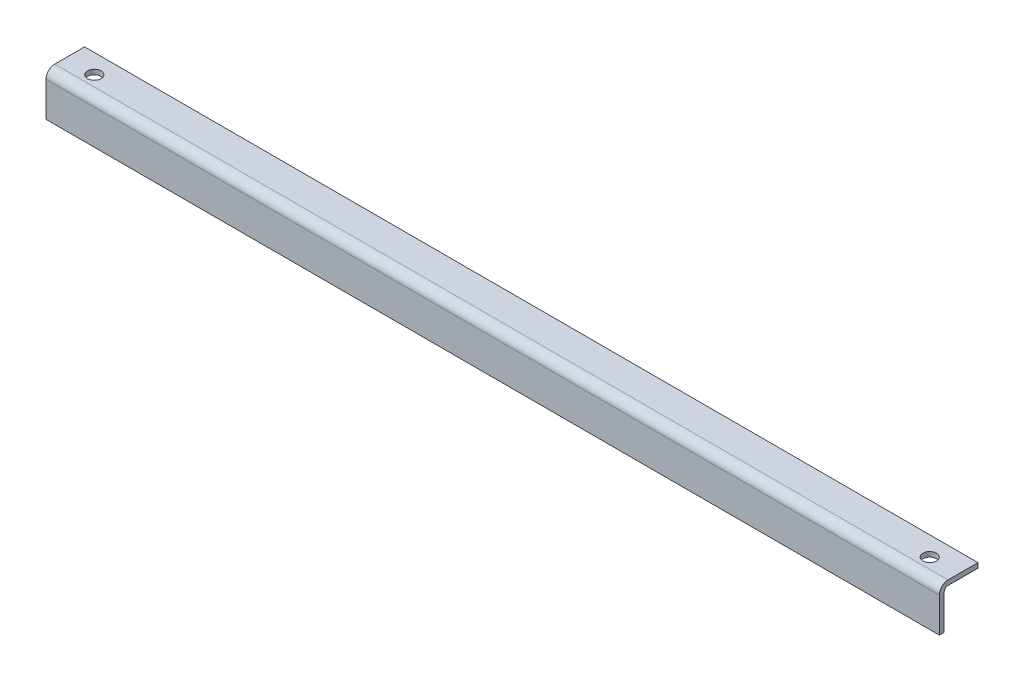
SolidWorks part; units mm, degrees
material "ASTM A36 Steel"
ref_plane "Front Plane" through (0, 0, 0) normal (0, 0, 1) x (1, 0, 0)
ref_plane "Top Plane" through (0, 0, 0) normal (0, 1, 0) x (1, 0, 0)
ref_plane "Right Plane" through (0, 0, 0) normal (1, 0, 0) x (0, 0, -1)
sketch "Sketch1" plane through (0, 0, 0) normal (0, 1, 0) x (1, 0, 0)
  line L1 (-231.2533, -10) -> (231.2533, -10)
  line L2 (-231.2533, -10) -> (-231.2533, 10)
  line L3 (-231.2533, 10) -> (231.2533, 10)
  line L4 (231.2533, -10) -> (231.2533, 10)
  line L5 (-231.2533, -10) -> (231.2533, 10) construction
  line L6 (-231.2533, 10) -> (231.2533, -10) construction
  point P0 (0, 0)
  dimension "D1" = 462.5066
  dimension "D2" = 20
extrude "Boss-Extrude1" add sketch "Sketch1" along normal blind 2.5
sketch "Sketch2" plane through (0, 2.5, 0) normal (0, 1, 0) x (1, 0, 0)
  line L0 (231.2533, -10) -> (231.2533, 10) construction
  line L1 (-231.2533, 10) -> (-231.2533, -10) construction
  circle A0 centre (216.2533, 0) radius 3.5
  circle A1 centre (-216.2533, 0) radius 3.5
  dimension "D1" = 7
  dimension "D2" = 15
  dimension "D3" = 7
  dimension "D4" = 15
extrude "Cut-Extrude1" cut sketch "Sketch2" against normal blind 2.5
sketch "Sketch3" plane through (0, 0, 0) normal (0, -1, 0) x (1, 0, 0)
  line L0 (-231.2533, -10) -> (-231.2533, 10) construction
  line L1 (231.2533, 10) -> (-231.2533, 10)
  line L2 (231.2533, 10) -> (231.2533, 7.5)
  line L3 (231.2533, 7.5) -> (-231.2533, 7.5)
  line L4 (-231.2533, 10) -> (-231.2533, 7.5)
  dimension "D1" = 2.5
extrude "Boss-Extrude2" add sketch "Sketch3" along normal blind 20
fillet "Fillet1" radius 2 1 edges at (0, 0, 7.5)
fillet "Fillet2" radius 4.5 1 edges at (0, 2.5, 10)
